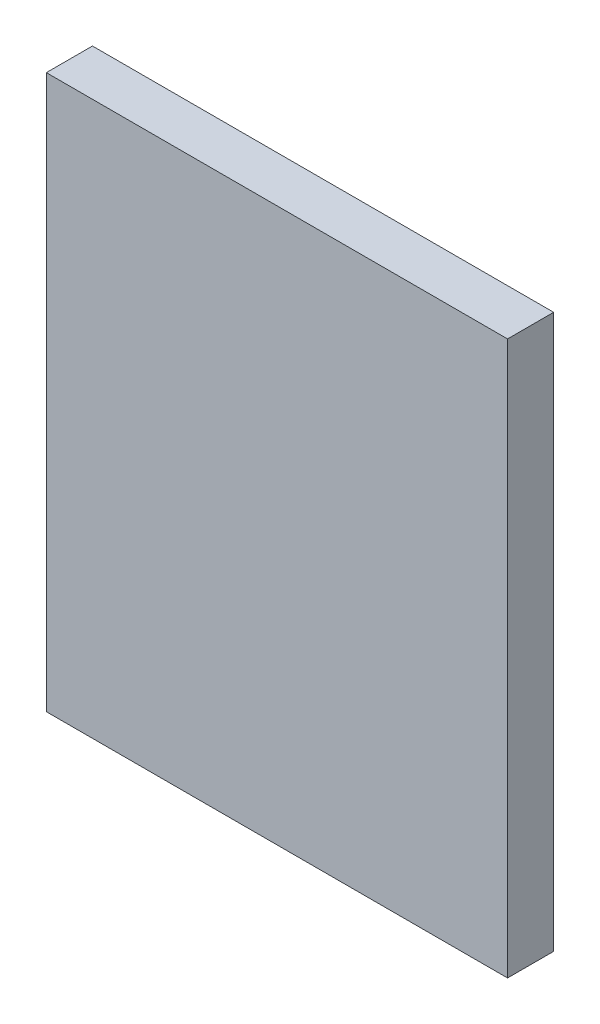
SolidWorks part; units mm, degrees
ref_plane "Front Plane" through (0, 0, 0) normal (0, 0, 1) x (1, 0, 0)
ref_plane "Top Plane" through (0, 0, 0) normal (0, 1, 0) x (1, 0, 0)
ref_plane "Right Plane" through (0, 0, 0) normal (1, 0, 0) x (0, 0, -1)
sketch "Sketch1" plane through (0, 0, 0) normal (0, 1, 0) x (1, 0, 0)
  line L1 (-127, 12.7) -> (127, 12.7)
  line L2 (-127, 12.7) -> (-127, -12.7)
  line L3 (-127, -12.7) -> (127, -12.7)
  line L4 (127, 12.7) -> (127, -12.7)
  line L5 (-127, 12.7) -> (127, -12.7) construction
  line L6 (-127, -12.7) -> (127, 12.7) construction
  point P0 (0, 0)
  dimension "D1" = 25.4
  dimension "D2" = 254
extrude "Boss-Extrude1" add sketch "Sketch1" along normal blind 304.8
